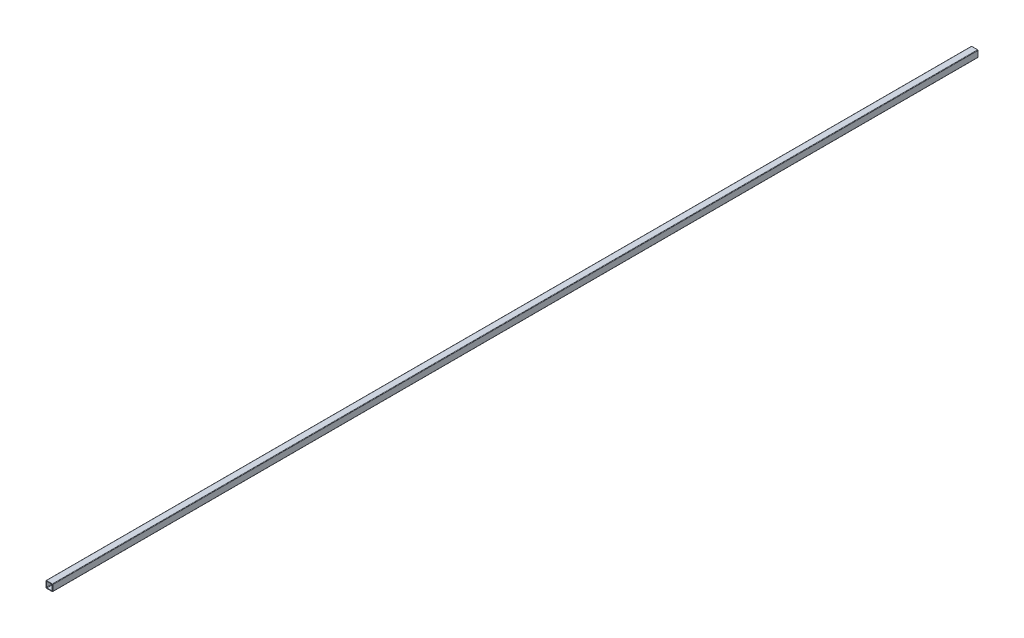
SolidWorks part; units mm, degrees
material "ASTM A500 Grade B Steel"
ref_plane "Front Plane" through (0, 0, 0) normal (0, 0, 1) x (1, 0, 0)
ref_plane "Top Plane" through (0, 0, 0) normal (0, 1, 0) x (1, 0, 0)
ref_plane "Right Plane" through (0, 0, 0) normal (1, 0, 0) x (0, 0, -1)
sketch "Sketch1" plane through (0, 0, 0) normal (0, 0, 1) x (1, 0, 0)
  line L0 (5.3086, -2.7686) -> (32.7914, -2.7686)
  line L1 (2.54, 0) -> (35.56, 0)
  line L2 (0, -2.54) -> (0, -35.56)
  line L3 (2.54, -38.1) -> (35.56, -38.1)
  line L4 (38.1, -2.54) -> (38.1, -35.56)
  line L5 (35.3314, -5.3086) -> (35.3314, -32.7914)
  line L6 (5.3086, -35.3314) -> (32.7914, -35.3314)
  line L7 (2.7686, -5.3086) -> (2.7686, -32.7914)
  line L8 (0, 0) -> (0, -38.1) construction
  line L9 (0, -38.1) -> (38.1, -38.1) construction
  line L10 (38.1, 0) -> (38.1, -38.1) construction
  line L11 (2.7686, -2.7686) -> (2.7686, -35.3314) construction
  line L12 (2.7686, -35.3314) -> (35.3314, -35.3314) construction
  line L13 (35.3314, -2.7686) -> (35.3314, -35.3314) construction
  line L14 (2.7686, -2.7686) -> (35.3314, -2.7686) construction
  line L15 (0, 0) -> (38.1, 0) construction
  arc A0 (0, -35.56) -> (2.54, -38.1) centre (2.54, -35.56) ccw
  arc A1 (38.1, -35.56) -> (35.56, -38.1) centre (35.56, -35.56) cw
  arc A2 (2.7686, -32.7914) -> (5.3086, -35.3314) centre (5.3086, -32.7914) ccw
  arc A3 (32.7914, -35.3314) -> (35.3314, -32.7914) centre (32.7914, -32.7914) ccw
  arc A4 (35.3314, -5.3086) -> (32.7914, -2.7686) centre (32.7914, -5.3086) ccw
  arc A5 (38.1, -2.54) -> (35.56, 0) centre (35.56, -2.54) ccw
  arc A6 (0, -2.54) -> (2.54, 0) centre (2.54, -2.54) cw
  arc A7 (5.3086, -2.7686) -> (2.7686, -5.3086) centre (5.3086, -5.3086) ccw
  point P12 (0, -38.1)
  dimension "D4" = 2.54
  dimension "D3" = 2.7686
extrude "Boss-Extrude1" add sketch "Sketch1" along normal blind 5243.8
fillet "Fillet1" radius 1 32 edges at (2.7686, -19.05, 0) (3.5125, -3.5125, 0) (19.05, -2.7686, 0) (34.5875, -3.5125, 0) (35.3314, -19.05, 0) (34.5875, -34.5875, 0) (19.05, -35.3314, 0) (3.5125, -34.5875, 0) (19.05, -38.1, 0) (37.3561, -37.3561, 0) (38.1, -19.05, 0) (37.3561, -0.7439, 0) (19.05, 0, 0) (0.7439, -0.7439, 0) (0, -19.05, 0) (0.7439, -37.3561, 0) (34.5875, -34.5875, 5243.8) (35.3314, -19.05, 5243.8) (34.5875, -3.5125, 5243.8) (19.05, -2.7686, 5243.8) (3.5125, -3.5125, 5243.8) (2.7686, -19.05, 5243.8) (3.5125, -34.5875, 5243.8) (19.05, -35.3314, 5243.8) (0, -19.05, 5243.8) (0.7439, -0.7439, 5243.8) (19.05, 0, 5243.8) (37.3561, -0.7439, 5243.8) (38.1, -19.05, 5243.8) (37.3561, -37.3561, 5243.8) (19.05, -38.1, 5243.8) (0.7439, -37.3561, 5243.8)
